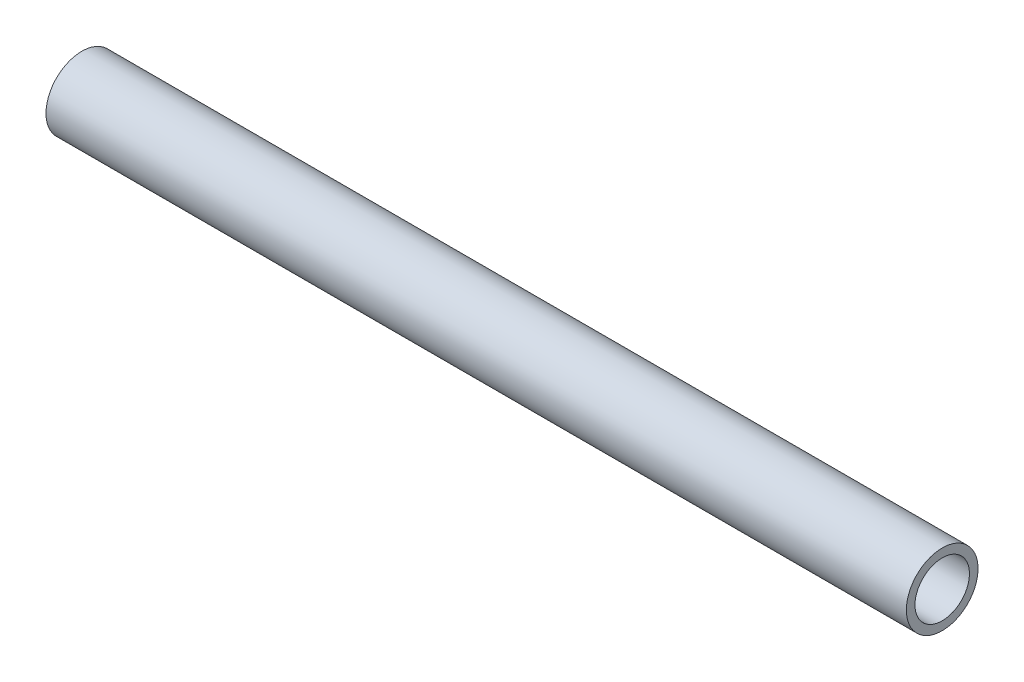
SolidWorks part; units mm, degrees
material "AISI 4130 Steel, annealed at 865C"
ref_plane "Front Plane" through (0, 0, 0) normal (0, 0, 1) x (1, 0, 0)
ref_plane "Top Plane" through (0, 0, 0) normal (0, 1, 0) x (1, 0, 0)
ref_plane "Right Plane" through (0, 0, 0) normal (1, 0, 0) x (0, 0, -1)
sketch "Sketch1" plane through (0, 0, 0) normal (1, 0, 0) x (0, 0, -1)
  circle A0 centre (0, 0) radius 12.7
  circle A1 centre (0, 0) radius 9.652
  dimension "D1" = 25.4
  dimension "D2" = 19.304
extrude "Boss-Extrude1" add sketch "Sketch1" along normal blind 304.8
